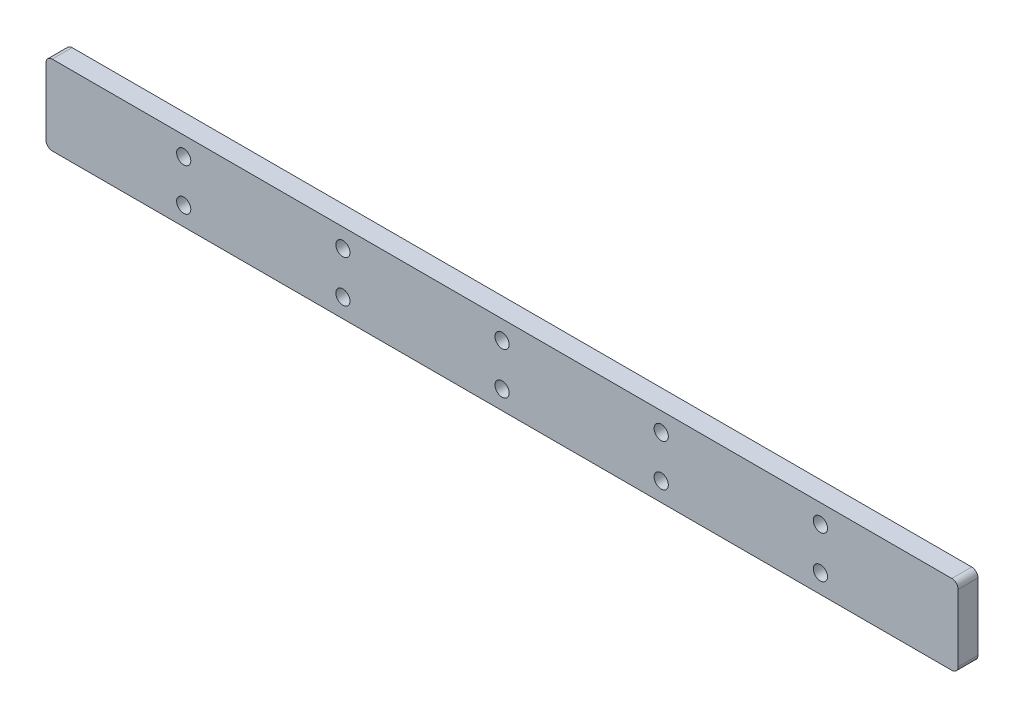
SolidWorks part; units mm, degrees
other "Markup1"
sketch "Sketch3" plane through (-72.775, -6.35, 3.175) normal (0, 0, 1) x (1, 0, 0)
material "6061 Alloy"
ref_plane "Front Plane" through (0, 0, 0) normal (0, 0, 1) x (1, 0, 0)
ref_plane "Top Plane" through (0, 0, 0) normal (0, 1, 0) x (1, 0, 0)
ref_plane "Right Plane" through (0, 0, 0) normal (1, 0, 0) x (0, 0, -1)
sketch "Sketch1" plane through (0, 0, 0) normal (0, 0, 1) x (1, 0, 0)
  line L1 (-72.775, 6.35) -> (72.775, 6.35)
  line L2 (-72.775, 6.35) -> (-72.775, -6.35)
  line L3 (-72.775, -6.35) -> (72.775, -6.35)
  line L4 (72.775, 6.35) -> (72.775, -6.35)
  point P4 (0, 6.35)
  point P6 (-72.775, 0)
  dimension "D1" = 145.55
  dimension "D2" = 12.7
extrude "Boss-Extrude1" add sketch "Sketch1" along normal blind 3.175
hole_wizard "#4-40 Tapped Hole1" positions "3DSketch1" profile "Sketch2" tap size "#4-40" standard "ANSI Inch" end condition through all
sketch3d "3DSketch1"
  line L3 (-72.775, 6.35, 3.175) -> (-72.775, -6.35, 3.175) construction
  line L6 (-72.775, -6.35, 3.175) -> (72.775, -6.35, 3.175) construction
  line L8 (72.775, 6.35, 3.175) -> (-72.775, 6.35, 3.175) construction
  point P0 (-50.8, 3.35, 3.175)
  point P2 (-50.8, -3.35, 3.175)
  dimension "D3" = 21.975
  dimension "D2" = 3
  dimension "D1" = 3
  dimension "D4" = 6.7
sketch "Sketch2" plane through (-50.8, 3.35, 3.175) normal (1, 0, 0) x (0, -1, 0)
  line L0 (0, 0) -> (0, 3.175)
  line L1 (0, 3.175) -> (1.1303, 3.175)
  line L2 (1.1303, 3.175) -> (1.1303, 0)
  line L5 (1.1303, 0) -> (0, 0)
  line L11 (0, -6.35) -> (0, 107.95) construction
  dimension "Thru Tap Drill Dia." = 2.2606
  dimension "Thru Tap Drill Depth" = 3.175
cosmetic thread "Hole Thread1"
cosmetic thread "Hole Thread2"
pattern_linear "LPattern1" count 5 spacing 25.4 along (1, 0, 0) of "#4-40 Tapped Hole1"
cosmetic thread "Hole Thread3"
cosmetic thread "Hole Thread4"
cosmetic thread "Hole Thread5"
cosmetic thread "Hole Thread6"
cosmetic thread "Hole Thread7"
cosmetic thread "Hole Thread8"
cosmetic thread "Hole Thread9"
cosmetic thread "Hole Thread10"
fillet "Fillet1" radius 1 4 edges at (72.775, -6.35, 1.5875) (72.775, 6.35, 1.5875) (-72.775, -6.35, 1.5875) (-72.775, 6.35, 1.5875)
equation "\"plate_height\"= 0.5in"
equation "\"D2@Sketch1\"=\"plate_height\""
equation "\"plate_length\"= 146.55 - 1"
equation "\"D1@Sketch1\"=\"plate_length\""
equation "\"D3@3DSketch1\"=(\"plate_length\"-(25.4*4))/2"
